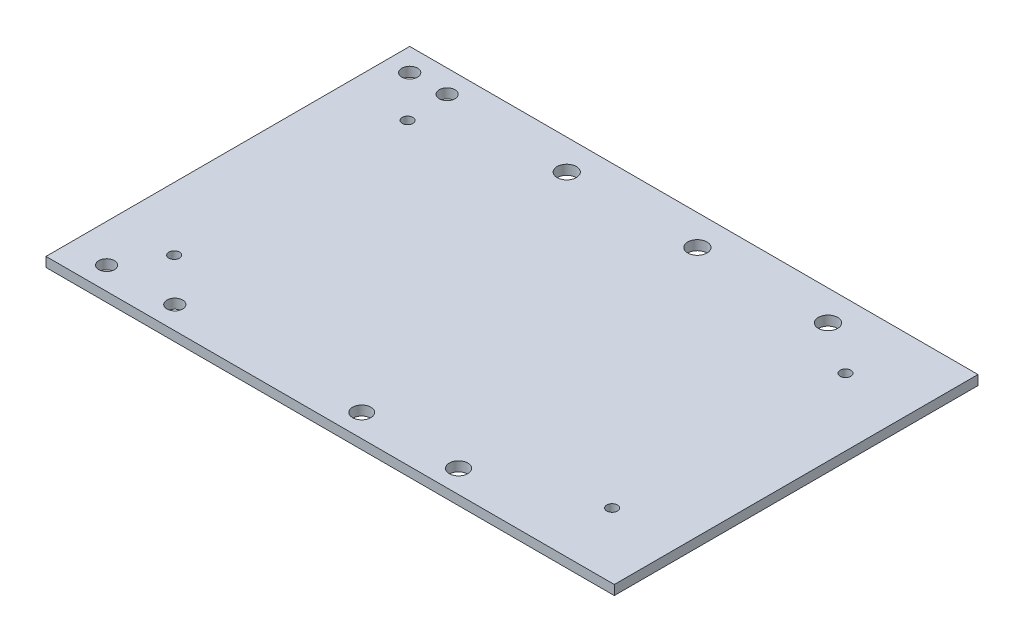
SolidWorks part; units mm, degrees
ref_plane "Front Plane" through (0, 0, 0) normal (0, 0, 1) x (1, 0, 0)
ref_plane "Top Plane" through (0, 0, 0) normal (0, 1, 0) x (1, 0, 0)
ref_plane "Right Plane" through (0, 0, 0) normal (1, 0, 0) x (0, 0, -1)
sketch "Sketch1" plane through (0, 0, 0) normal (0, 1, 0) x (1, 0, 0)
  line L0 (15, -15) -> (39.6804, -15) construction
  line L1 (0, 0) -> (375, 0)
  line L2 (0, 0) -> (0, -240)
  line L3 (0, -240) -> (375, -240)
  line L4 (375, 0) -> (375, -240)
  line L5 (25, -225) -> (70, -225) construction
  line L7 (193.34, -225) -> (257.2443, -225) construction
  line L8 (41.5666, -43) -> (41.5666, -197) construction
  line L9 (41.5666, -197) -> (330.5666, -197) construction
  line L10 (330.5666, -197) -> (330.5666, -43) construction
  line L11 (330.5666, -43) -> (41.5666, -43) construction
  line L12 (41.5666, -43) -> (33.5666, -43) construction
  line L13 (330.5666, -43) -> (330.5666, -35) construction
  line L14 (330.5666, -197) -> (330.5666, -205) construction
  circle A0 centre (15, -15) radius 5.1815
  circle A1 centre (39.6804, -15) radius 5.1815
  circle A2 centre (25, -225) radius 5.1815
  circle A3 centre (70, -225) radius 5.1815
  circle A6 centre (193.34, -225) radius 6.0182
  circle A7 centre (257.2443, -225) radius 6.107
  circle A8 centre (41.5666, -43) radius 3.5
  circle A9 centre (41.5666, -197) radius 3.5
  circle A10 centre (330.5666, -197) radius 3.5
  circle A11 centre (330.5666, -43) radius 3.5
  circle A12 centre (209.82, -20) radius 6.35
  circle A13 centre (123.6221, -20) radius 6.35 construction
  circle A14 centre (123.6221, -20) radius 6.35
  circle A15 centre (296.0179, -20) radius 6.35 construction
  circle A16 centre (296.0179, -20) radius 6.35
  point P10 (330.5666, -120)
  point P11 (375, -120)
  dimension "D10" = 7
  dimension "D1" = 45
  dimension "D2" = 25
  dimension "D3" = 15
  dimension "D4" = 15
  dimension "D5" = 15
  dimension "D6" = 375
  dimension "D7" = 240
  dimension "D8" = 209.82
  dimension "D9" = 20
  dimension "D11" = 289
  dimension "D12" = 154
  dimension "D13" = 8
  dimension "D14" = 33.5666
  dimension "D15" = 8
  dimension "D17" = 8
extrude "Boss-Extrude1" add sketch "Sketch1" against normal blind 6.35
